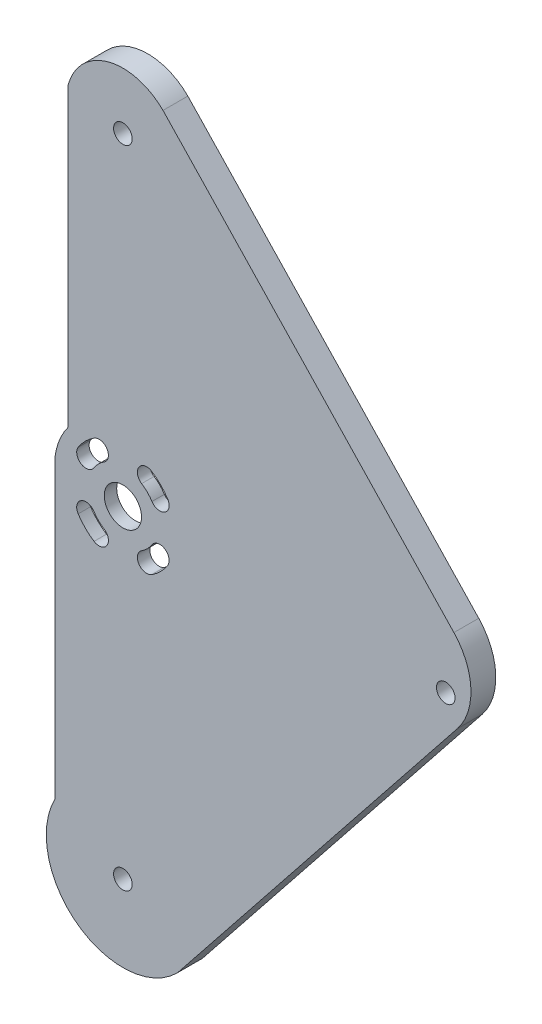
SolidWorks part; units mm, degrees
ref_plane "前视基准面" through (0, 0, 0) normal (0, 0, 1) x (1, 0, 0)
ref_plane "上视基准面" through (0, 0, 0) normal (0, 1, 0) x (1, 0, 0)
ref_plane "右视基准面" through (0, 0, 0) normal (1, 0, 0) x (0, 0, -1)
sketch "草图1" plane through (0, 0, 0) normal (0, 0, 1) x (1, 0, 0)
  line L0 (1791.9751, 1614.3835) -> (1791.9751, 1566.6287)
  line L1 (1789.8715, 1561.5082) -> (1789.8715, 1513.7534)
  line L2 (1807.2571, 1618.4717) -> (1860.0947, 1562.7534)
  line L3 (1860.0947, 1562.7534) -> (1809.6082, 1499.3687)
  circle A0 centre (1800.7974, 1560.012) radius 3
  circle A1 centre (1800.7974, 1612.012) radius 1.5
  circle A2 centre (1852.7974, 1560.012) radius 1.5
  circle A3 centre (1800.7974, 1508.012) radius 1.5
  arc A4 (1789.8715, 1513.7534) -> (1809.6082, 1499.3687) centre (1800.7974, 1508.012) ccw
  arc A5 (1807.2571, 1618.4717) -> (1791.9751, 1614.3835) centre (1800.7974, 1612.012) ccw
  arc A7 (1791.9751, 1566.6287) -> (1789.8715, 1561.5082) centre (1800.7974, 1560.012) ccw
  arc A8 (1805.4433, 1552.8093) -> (1808.0001, 1555.3661) centre (1800.7974, 1560.012) ccw
  arc A9 (1808.0001, 1564.6579) -> (1805.4433, 1567.2147) centre (1800.7974, 1560.012) ccw
  arc A10 (1796.1515, 1567.2147) -> (1793.5947, 1564.6579) centre (1800.7974, 1560.012) ccw
  arc A11 (1793.5947, 1555.3661) -> (1796.1515, 1552.8093) centre (1800.7974, 1560.012) ccw
  arc A12 (1803.8171, 1555.3304) -> (1805.479, 1556.9923) centre (1800.7974, 1560.012) ccw
  arc A13 (1805.479, 1563.0318) -> (1803.8171, 1564.6937) centre (1800.7974, 1560.012) ccw
  arc A14 (1797.7776, 1564.6937) -> (1796.1157, 1563.0318) centre (1800.7974, 1560.012) ccw
  arc A15 (1796.1157, 1556.9923) -> (1797.7776, 1555.3304) centre (1800.7974, 1560.012) ccw
  arc A16 (1805.4433, 1567.2147) -> (1803.8171, 1564.6937) centre (1804.6302, 1565.9542) ccw
  arc A17 (1805.479, 1563.0318) -> (1808.0001, 1564.6579) centre (1806.7395, 1563.8448) ccw
  arc A18 (1797.7776, 1564.6937) -> (1796.1515, 1567.2147) centre (1796.9645, 1565.9542) ccw
  arc A19 (1793.5947, 1564.6579) -> (1796.1157, 1563.0318) centre (1794.8552, 1563.8448) ccw
  arc A20 (1796.1157, 1556.9923) -> (1793.5947, 1555.3661) centre (1794.8552, 1556.1792) ccw
  arc A21 (1796.1515, 1552.8093) -> (1797.7776, 1555.3304) centre (1796.9645, 1554.0698) ccw
  arc A22 (1803.8171, 1555.3304) -> (1805.4433, 1552.8093) centre (1804.6302, 1554.0698) ccw
  arc A23 (1808.0001, 1555.3661) -> (1805.479, 1556.9923) centre (1806.7395, 1556.1792) ccw
  dimension "D8" = 52
  dimension "D1" = 52
  dimension "D3" = 4
  dimension "D2" = 52
extrude "凸台-拉伸1" add sketch "草图1" along normal blind 4
sketch "草图3" plane through (0, 0, 0) normal (0, 0, -1) x (-1, 0, 0)
  circle A0 centre (-1800.7974, 1560.012) radius 13
extrude "切除-拉伸2" cut sketch "草图3" against normal blind 2
fillet "圆角1" radius 10 1 edges at (1860.0947, 1562.7534, 2)
